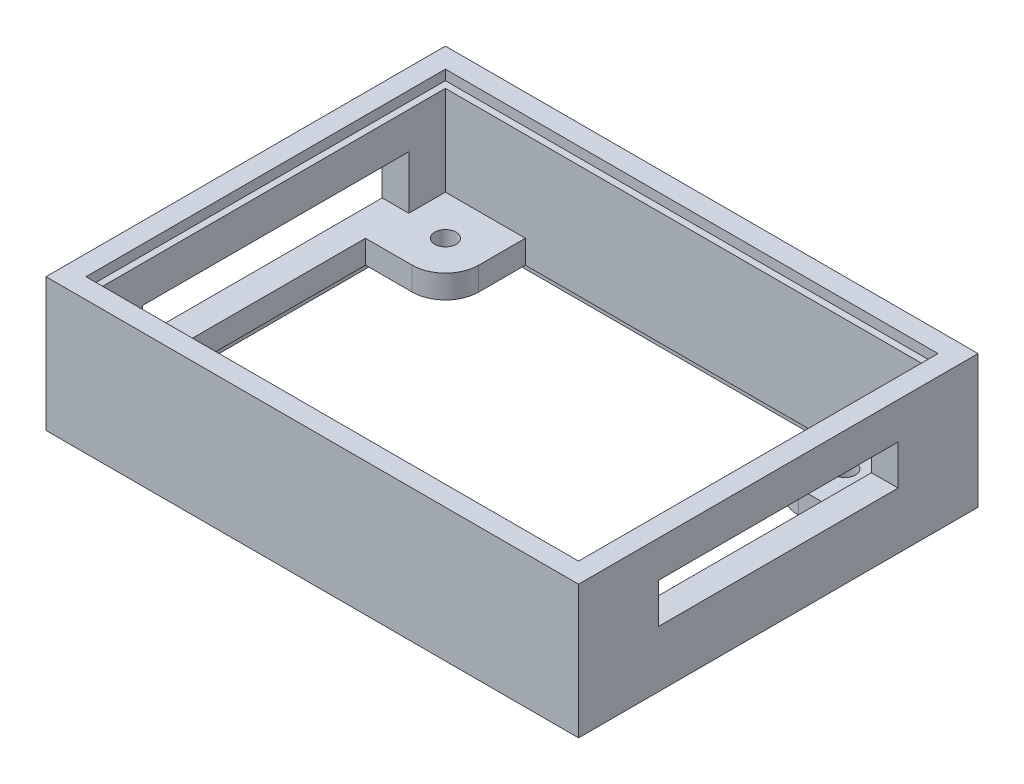
SolidWorks part; units mm, degrees
ref_plane "前视基准面" through (0, 0, 0) normal (0, 0, 1) x (1, 0, 0)
ref_plane "上视基准面" through (0, 0, 0) normal (0, 1, 0) x (1, 0, 0)
ref_plane "右视基准面" through (0, 0, 0) normal (1, 0, 0) x (0, 0, -1)
sketch "草图1" plane through (0, 0, 0) normal (0, 1, 0) x (1, 0, 0)
  line L1 (40, -30) -> (-40, -30)
  line L2 (40, -30) -> (40, 30)
  line L3 (40, 30) -> (-40, 30)
  line L4 (-40, -30) -> (-40, 30)
  line L5 (40, -30) -> (-40, 30) construction
  line L6 (40, 30) -> (-40, -30) construction
  point P0 (0, 0)
  dimension "D1" = 60
  dimension "D2" = 80
extrude "凸台-拉伸1" add sketch "草图1" along normal blind 20
sketch "草图2" plane through (0, 20, 0) normal (0, 1, 0) x (1, 0, 0)
  line L1 (36, -26) -> (-36, -26)
  line L2 (36, -26) -> (36, 26)
  line L3 (36, 26) -> (-36, 26)
  line L4 (-36, -26) -> (-36, 26)
  line L5 (36, -26) -> (-36, 26) construction
  line L6 (36, 26) -> (-36, -26) construction
  point P0 (0, 0)
  dimension "D1" = 52
  dimension "D2" = 72
extrude "切除-拉伸1" cut sketch "草图2" against normal blind 15
sketch "草图3" plane through (0, 5, 0) normal (0, 1, 0) x (1, 0, 0)
  line L0 (-36, -26) -> (36, -26) construction
  line L1 (-36, 26) -> (-24, 26) construction
  line L2 (-36, 26) -> (-36, 14) construction
  line L3 (-36, 14) -> (-24, 14) construction
  line L4 (-24, 26) -> (-24, 14) construction
  line L5 (36, -26) -> (36, 26) construction
  line L6 (-36, 26) -> (-36, -26) construction
  line L7 (36, 26) -> (-36, 26) construction
  line L8 (-36, -26) -> (36, -26) construction
  line L9 (36, -26) -> (36, 26) construction
  line L10 (-36, 26) -> (-36, -26) construction
  line L11 (36, 26) -> (-36, 26) construction
  line L12 (-24, 14) -> (-36, 14)
  line L13 (36, -14) -> (24, -14)
  line L14 (36, -14) -> (36, 14)
  line L15 (36, 14) -> (24, 14)
  line L16 (-36, -14) -> (-36, 14)
  line L17 (36, -14) -> (-36, 14) construction
  line L18 (36, 14) -> (-36, -14) construction
  line L19 (24, -26) -> (-24, -26)
  line L20 (24, -26) -> (24, -14)
  line L21 (24, 26) -> (-24, 26)
  line L22 (-24, -26) -> (-24, -14)
  line L23 (24, -26) -> (-24, 26) construction
  line L24 (24, 26) -> (-24, -26) construction
  line L25 (-24, 14) -> (-24, 26)
  line L26 (24, 14) -> (24, 26)
  line L27 (-24, -14) -> (-36, -14)
  point P7 (0, 0)
  point P10 (0, 0)
  dimension "D1" = 12
  dimension "D2" = 12
extrude "切除-拉伸2" cut sketch "草图3" against normal through all
sketch "草图4" plane through (0, 5, 0) normal (0, 1, 0) x (1, 0, 0)
  line L1 (30, -20) -> (-30, -20) construction
  line L2 (30, -20) -> (30, 20) construction
  line L3 (30, 20) -> (-30, 20) construction
  line L4 (-30, -20) -> (-30, 20) construction
  line L5 (30, -20) -> (-30, 20) construction
  line L6 (30, 20) -> (-30, -20) construction
  circle A0 centre (-30, 20) radius 1.6
  point P0 (0, 0)
  dimension "D3" = 3.2
  dimension "D1" = 40
  dimension "D2" = 60
extrude "切除-拉伸3" cut sketch "草图4" against normal through all
pattern_linear "阵列(线性)1" count 2 spacing 60 along (1, 0, 0) count 2 spacing 40 along (0, 0, 1) of "切除-拉伸3"
fillet "圆角1" radius 5 4 edges at (24, 2.5, 14) (-24, 2.5, 14) (24, 2.5, -14) (-24, 2.5, -14)
sketch "草图5" plane through (0, 0, 0) normal (0, -1, 0) x (1, 0, 0)
  line L1 (36, -26) -> (-36, -26)
  line L2 (36, -26) -> (36, 26)
  line L3 (36, 26) -> (-36, 26)
  line L4 (-36, -26) -> (-36, 26)
  line L5 (36, -26) -> (-36, 26) construction
  line L6 (36, 26) -> (-36, -26) construction
  point P0 (0, 0)
  dimension "D1" = 52
  dimension "D2" = 72
extrude "切除-拉伸4" cut sketch "草图5" against normal blind 1.5
sketch "草图6" plane through (-36, 0, 0) normal (1, 0, 0) x (0, 0, -1)
  line L0 (20.5, 13) -> (-19.5, 13)
  line L1 (20.5, 13) -> (20.5, 5)
  line L2 (-19.5, 13) -> (-19.5, 5)
  line L3 (20.5, 5) -> (-19.5, 5)
  line L4 (20.5, 13) -> (-19.5, 5) construction
  line L5 (-19.5, 13) -> (20.5, 5) construction
  line L6 (26, 5) -> (14, 5) construction
  line L8 (26, 5) -> (26, 20) construction
  point P1 (0.5, 9)
  dimension "D1" = 8
  dimension "D2" = 40
  dimension "D3" = 5.5
extrude "切除-拉伸7" cut sketch "草图6" against normal through all
sketch "草图7" plane through (36, 0, 0) normal (-1, 0, 0) x (0, 0, 1)
  line L0 (-26, 5) -> (-26, 20) construction
  line L1 (-18, 14.5) -> (18, 14.5)
  line L2 (-18, 14.5) -> (-18, 8.5)
  line L3 (-18, 8.5) -> (18, 8.5)
  line L4 (18, 14.5) -> (18, 8.5)
  line L5 (-14, 5) -> (-26, 5) construction
  dimension "D1" = 36
  dimension "D2" = 6
  dimension "D3" = 8
  dimension "D4" = 3.5
extrude "切除-拉伸8" cut sketch "草图7" against normal through all
sketch "草图8" plane through (0, 20, 0) normal (0, 1, 0) x (1, 0, 0)
  line L1 (37, -27) -> (-37, -27)
  line L2 (37, -27) -> (37, 27)
  line L3 (37, 27) -> (-37, 27)
  line L4 (-37, -27) -> (-37, 27)
  line L5 (37, -27) -> (-37, 27) construction
  line L6 (37, 27) -> (-37, -27) construction
  point P0 (0, 0)
  dimension "D1" = 74
  dimension "D2" = 54
extrude "切除-拉伸9" cut sketch "草图8" against normal blind 1.5
sketch "草图9" plane through (0, 0, 0) normal (0, -1, 0) x (1, 0, 0)
  line L1 (37, -27) -> (-37, -27)
  line L2 (37, -27) -> (37, 27)
  line L3 (37, 27) -> (-37, 27)
  line L4 (-37, -27) -> (-37, 27)
  line L5 (37, -27) -> (-37, 27) construction
  line L6 (37, 27) -> (-37, -27) construction
  point P0 (0, 0)
  dimension "D1" = 54
  dimension "D2" = 74
extrude "切除-拉伸10" cut sketch "草图9" against normal blind 1.5
